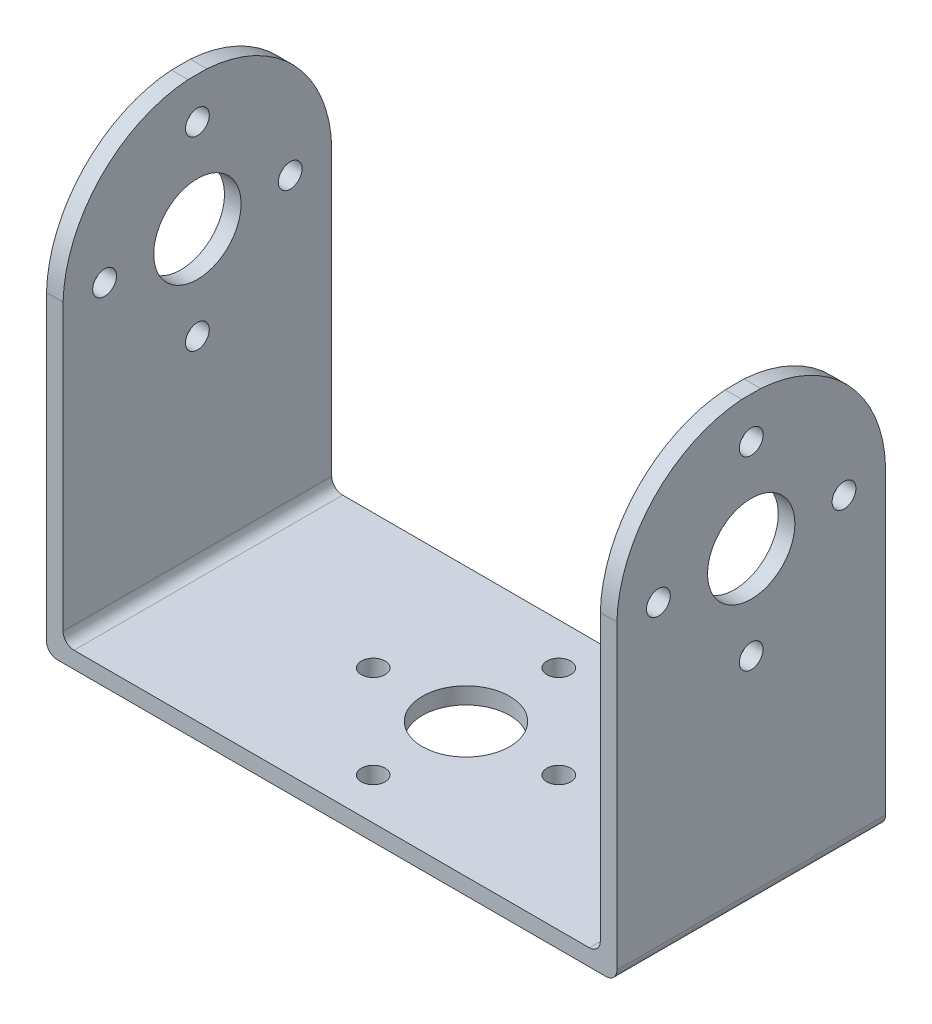
SolidWorks part; units mm, degrees
material "1060 Alloy"
ref_plane "Front" through (0, 0, 0) normal (0, 0, 1) x (1, 0, 0)
ref_plane "Top" through (0, 0, 0) normal (0, 1, 0) x (1, 0, 0)
ref_plane "Right" through (0, 0, 0) normal (1, 0, 0) x (0, 0, -1)
sketch "Sketch1" plane through (0, 0, 0) normal (0, 0, 1) x (1, 0, 0)
  line L0 (-26.125, 58.34) -> (-26.125, 0)
  line L1 (-26.125, 0) -> (26.125, 0)
  line L2 (26.125, 0) -> (26.125, 58.34)
  line L3 (26.125, 58.34) -> (24.605, 58.34)
  line L4 (24.605, 58.34) -> (24.605, 1.52)
  line L5 (24.605, 1.52) -> (-24.605, 1.52)
  line L6 (-24.605, 1.52) -> (-24.605, 58.34)
  line L7 (-24.605, 58.34) -> (-26.125, 58.34)
  line L8 (0, 0) -> (0, 39.8855) construction
  dimension "D1" = 58.34
  dimension "D2" = 52.25
  dimension "D3" = 1.52
  dimension "D4" = 1.52
  dimension "D5" = 1.52
extrude "Boss-Extrude1" add sketch "Sketch1" along normal blind 24.61
ref_plane "Plane1" through (-26.125, 0, 0) normal (-1, 0, 0) x (0, 0, 1)
sketch "Sketch2" plane through (-26.125, 0, 0) normal (-1, 0, 0) x (0, 0, 1)
  line L0 (12.305, 58.34) -> (12.305, 0) construction
  line L1 (24.61, 58.34) -> (0, 58.34) construction
  line L2 (-0.005, 28.28) -> (24.615, 28.28) construction
  line L3 (-0.005, 28.28) -> (-0.003, 40.56)
  line L6 (24.613, 40.56) -> (24.615, 28.28)
  line L7 (24.61, 0) -> (0, 0) construction
  line L8 (11.4461, 40.56) -> (-0.003, 40.56)
  line L9 (13.1639, 40.56) -> (24.613, 40.56)
  arc A0 (24.615, 28.28) -> (13.1639, 40.56) centre (12.305, 28.28) ccw
  circle A1 centre (12.305, 28.28) radius 4
  arc A2 (11.4461, 40.56) -> (-0.005, 28.28) centre (12.305, 28.28) ccw
  point P6 (12.305, 40.59)
  dimension "D2" = 28.28
  dimension "D3" = 8
extrude "Cut-Extrude5" cut sketch "Sketch2" against normal blind 20
mirror "Mirror1" about plane through (0, 0, 0) normal (1, 0, 0) of "Cut-Extrude5"
sketch "Sketch4" plane through (-26.125, 0, 0) normal (-1, 0, 0) x (0, 0, 1)
  circle A0 centre (12.305, 36.78) radius 1.09
  circle A1 centre (12.305, 28.28) radius 4 construction
  dimension "D1" = 2.18
  dimension "D2" = 8.5
  dimension "D3" = 36.78
extrude "Cut-Extrude6" cut sketch "Sketch4" against normal blind 100
pattern_circular "CirPattern1" count 4 over 360 about axis through (0, 28.28, 12.305) along (1, 0, 0) of "Cut-Extrude6"
ref_plane "Plane2" through (0, 1.52, 0) normal (0, 1, 0) x (1, 0, 0)
sketch "Sketch5" plane through (0, 1.52, 0) normal (0, 1, 0) x (1, 0, 0)
  line L0 (26.125, -12.305) -> (-26.125, -12.305) construction
  line L1 (26.125, -24.61) -> (26.125, 0) construction
  line L2 (-26.125, 13.5355) -> (-26.125, -13.5355) construction
  circle A0 centre (0, -12.305) radius 4
  dimension "D1" = 8
extrude "Cut-Extrude7" cut sketch "Sketch5" against normal mid plane 100
sketch "Sketch6" plane through (0, 1.52, 0) normal (0, 1, 0) x (1, 0, 0)
  circle A0 centre (0, -3.805) radius 1.09
  circle A1 centre (0, -12.305) radius 4 construction
  dimension "D1" = 2.18
  dimension "D2" = 8.5
  dimension "D3" = 3.805
extrude "Cut-Extrude8" cut sketch "Sketch6" against normal mid plane 100
pattern_circular "CirPattern2" count 4 over 360 about axis through (0, 0, 12.305) along (0, 1, 0) of "Cut-Extrude8"
fillet "Fillet1" radius 1 4 edges at (26.125, 0, 12.305) (-26.125, 0, 12.305) (24.605, 1.52, 12.305) (-24.605, 1.52, 12.305)
sketch "Sketch7" plane through (-26.125, 0, 0) normal (-1, 0, 0) x (0, 0, 1)
  line L0 (0, 40.56) -> (24.61, 40.56)
  line L1 (24.61, 40.56) -> (24.61, 58.34)
  line L2 (24.61, 58.34) -> (0, 58.34)
  line L3 (0, 58.34) -> (0, 40.56)
extrude "Cut-Extrude9" cut sketch "Sketch7" against normal blind 100
